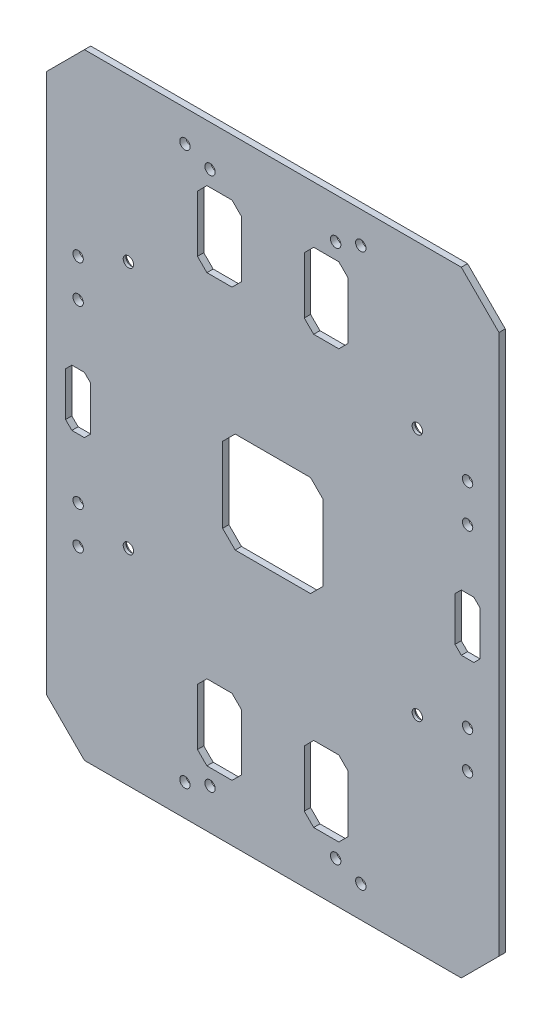
SolidWorks part; units mm, degrees
material "碳纤维板_1600kg_m3"
ref_plane "前视基准面" through (0, 0, 0) normal (0, 0, 1) x (1, 0, 0)
ref_plane "上视基准面" through (0, 0, 0) normal (0, 1, 0) x (1, 0, 0)
ref_plane "右视基准面" through (0, 0, 0) normal (1, 0, 0) x (0, 0, -1)
other "Configuration Table"
sketch "草图2" plane through (0, 0, 0) normal (0, 0, 1) x (1, 0, 0)
  circle A0 centre (-32.5, -46) radius 2.75
  circle A1 centre (-32.5, 46) radius 2.75
  circle A2 centre (46.5, -46) radius 2.75
  circle A3 centre (46.5, 46) radius 2.75
sketch "草图3" plane through (0, 0, 0) normal (0, 0, 1) x (1, 0, 0)
  circle A0 centre (-62, -28) radius 1.65
  circle A1 centre (-28, -62) radius 1.65
  circle A2 centre (-62, 28) radius 1.65
  circle A3 centre (-28, 62) radius 1.65
  circle A4 centre (62, -28) radius 1.65
  circle A5 centre (28, -62) radius 1.65
  circle A6 centre (62, 28) radius 1.65
  circle A7 centre (28, 62) radius 1.65
sketch "草图4" plane through (0, 0, 0) normal (0, 0, 1) x (1, 0, 0)
  line L0 (-40, -72) -> (-30, -72)
  line L1 (-30, -72) -> (-28, -70)
  line L2 (-28, -70) -> (-28, -60)
  line L3 (-28, -60) -> (-30, -58)
  line L4 (-30, -58) -> (-40, -58)
  line L5 (-40, -58) -> (-42, -60)
  line L6 (-42, -60) -> (-42, -70)
  line L7 (-42, -70) -> (-40, -72)
  line L8 (-40, 58) -> (-30, 58)
  line L9 (-30, 58) -> (-28, 60)
  line L10 (-28, 60) -> (-28, 70)
  line L11 (-28, 70) -> (-30, 72)
  line L12 (-30, 72) -> (-40, 72)
  line L13 (-40, 72) -> (-42, 70)
  line L14 (-42, 70) -> (-42, 60)
  line L15 (-42, 60) -> (-40, 58)
  line L16 (30, -72) -> (40, -72)
  line L17 (40, -72) -> (42, -70)
  line L18 (42, -70) -> (42, -60)
  line L19 (42, -60) -> (40, -58)
  line L20 (40, -58) -> (30, -58)
  line L21 (30, -58) -> (28, -60)
  line L22 (28, -60) -> (28, -70)
  line L23 (28, -70) -> (30, -72)
  line L24 (30, 58) -> (40, 58)
  line L25 (40, 58) -> (42, 60)
  line L26 (42, 60) -> (42, 70)
  line L27 (42, 70) -> (40, 72)
  line L28 (40, 72) -> (30, 72)
  line L29 (30, 72) -> (28, 70)
  line L30 (28, 70) -> (28, 60)
  line L31 (28, 60) -> (30, 58)
sketch "草图5" plane through (0, 0, 0) normal (0, 0, 1) x (1, 0, 0)
  circle A0 centre (-35, -62) radius 1.65
  circle A1 centre (-35, 62) radius 1.65
  circle A2 centre (35, -62) radius 1.65
  circle A3 centre (35, 62) radius 1.65
sketch "草图6" plane through (0, 0, 0) normal (0, 0, 1) x (1, 0, 0)
  circle A0 centre (28, 62) radius 1.75
  circle A1 centre (-28, 62) radius 1.75
  circle A2 centre (28, -62) radius 1.75
  circle A3 centre (-28, -62) radius 1.75
sketch "草图7" plane through (0, 0, 0) normal (0, 0, 1) x (1, 0, 0)
  line L0 (-60, -98) -> (60, -98)
  line L1 (60, -98) -> (72, -86)
  line L2 (72, -86) -> (72, 86)
  line L3 (72, 86) -> (60, 98)
  line L4 (60, 98) -> (-60, 98)
  line L5 (-60, 98) -> (-72, 86)
  line L6 (-72, 86) -> (-72, -86)
  line L7 (-72, -86) -> (-60, -98)
  line L8 (-64, -9) -> (-60, -9)
  line L9 (-60, -9) -> (-58, -7)
  line L10 (-58, -7) -> (-58, 7)
  line L11 (-58, 7) -> (-60, 9)
  line L12 (-60, 9) -> (-64, 9)
  line L13 (-64, 9) -> (-66, 7)
  line L14 (-66, 7) -> (-66, -7)
  line L15 (-66, -7) -> (-64, -9)
  line L16 (-21, 56) -> (-13, 56)
  line L17 (-13, 56) -> (-10, 59)
  line L18 (-10, 59) -> (-10, 77)
  line L19 (-10, 77) -> (-13, 80)
  line L20 (-13, 80) -> (-21, 80)
  line L21 (-21, 80) -> (-24, 77)
  line L22 (-24, 77) -> (-24, 59)
  line L23 (-24, 59) -> (-21, 56)
  line L24 (-21, -80) -> (-13, -80)
  line L25 (-13, -80) -> (-10, -77)
  line L26 (-10, -77) -> (-10, -59)
  line L27 (-10, -59) -> (-13, -56)
  line L28 (-13, -56) -> (-21, -56)
  line L29 (-21, -56) -> (-24, -59)
  line L30 (-24, -59) -> (-24, -77)
  line L31 (-24, -77) -> (-21, -80)
  line L32 (60, -9) -> (64, -9)
  line L33 (64, -9) -> (66, -7)
  line L34 (66, -7) -> (66, 7)
  line L35 (66, 7) -> (64, 9)
  line L36 (64, 9) -> (60, 9)
  line L37 (60, 9) -> (58, 7)
  line L38 (58, 7) -> (58, -7)
  line L39 (58, -7) -> (60, -9)
  line L40 (13, 56) -> (21, 56)
  line L41 (21, 56) -> (24, 59)
  line L42 (24, 59) -> (24, 77)
  line L43 (24, 77) -> (21, 80)
  line L44 (21, 80) -> (13, 80)
  line L45 (13, 80) -> (10, 77)
  line L46 (10, 77) -> (10, 59)
  line L47 (10, 59) -> (13, 56)
  line L48 (13, -80) -> (21, -80)
  line L49 (21, -80) -> (24, -77)
  line L50 (24, -77) -> (24, -59)
  line L51 (24, -59) -> (21, -56)
  line L52 (21, -56) -> (13, -56)
  line L53 (13, -56) -> (10, -59)
  line L54 (10, -59) -> (10, -77)
  line L55 (10, -77) -> (13, -80)
  line L56 (-12, -16) -> (12, -16)
  line L57 (12, -16) -> (16, -12)
  line L58 (16, -12) -> (16, 12)
  line L59 (16, 12) -> (12, 16)
  line L60 (12, 16) -> (-12, 16)
  line L61 (-12, 16) -> (-16, 12)
  line L62 (-16, 12) -> (-16, -12)
  line L63 (-16, -12) -> (-12, -16)
  circle A0 centre (-20, -85) radius 1.65
  circle A1 centre (-62, -28) radius 1.65
  circle A2 centre (-28, -88) radius 1.65
  circle A3 centre (-62, -40) radius 1.65
  circle A4 centre (-20, 85) radius 1.65
  circle A5 centre (-62, 28) radius 1.65
  circle A6 centre (-28, 88) radius 1.65
  circle A7 centre (-62, 40) radius 1.65
  circle A8 centre (20, -85) radius 1.65
  circle A9 centre (62, -28) radius 1.65
  circle A10 centre (28, -88) radius 1.65
  circle A11 centre (62, -40) radius 1.65
  circle A12 centre (20, 85) radius 1.65
  circle A13 centre (62, 28) radius 1.65
  circle A14 centre (28, 88) radius 1.65
  circle A15 centre (62, 40) radius 1.65
  circle A16 centre (-46, -32.5) radius 1.65
  circle A17 centre (-46, 46.5) radius 1.65
  circle A18 centre (46, -32.5) radius 1.65
  circle A19 centre (46, 46.5) radius 1.65
extrude "前后柱位及对地相机中央检修窗" add sketch "草图7" along normal blind 2
sketch "草图8" plane through (0, 0, 0) normal (0, 0, 1) x (1, 0, 0)
  circle A0 centre (-46, -32.5) radius 2.75
  circle A1 centre (-46, 46.5) radius 2.75
  circle A2 centre (46, -32.5) radius 2.75
  circle A3 centre (46, 46.5) radius 2.75
extrude "上位机沉头螺钉底面避让" cut sketch "草图8" along normal blind 1.1
